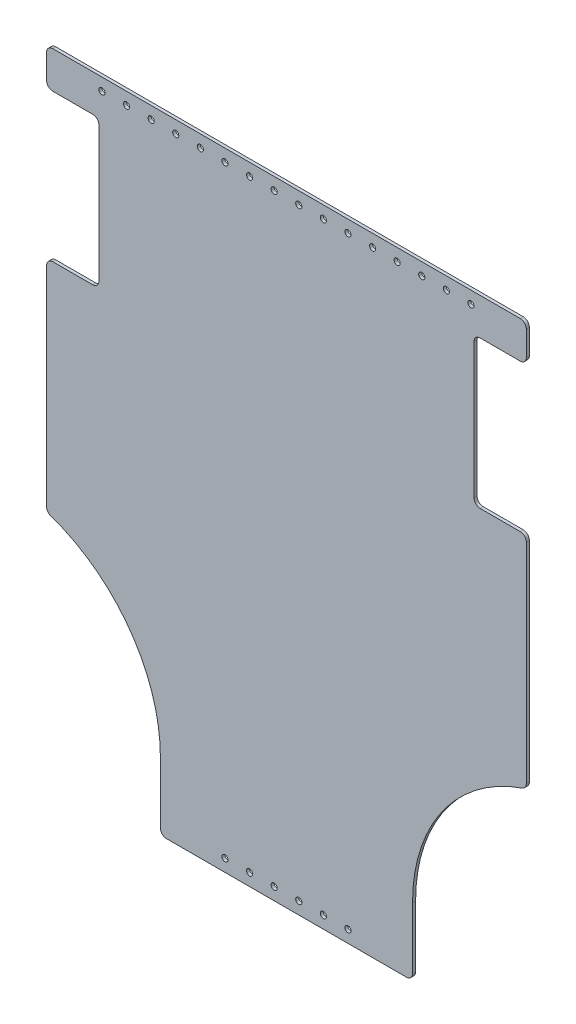
SolidWorks part; units mm, degrees
material "6061-T6 (SS)"
ref_plane "Front Plane" through (0, 0, 0) normal (0, 0, 1) x (1, 0, 0)
ref_plane "Top Plane" through (0, 0, 0) normal (0, 1, 0) x (1, 0, 0)
ref_plane "Right Plane" through (0, 0, 0) normal (1, 0, 0) x (0, 0, -1)
sketch "Sketch1" plane through (0, 0, 0) normal (0, 0, 1) x (1, 0, 0)
  line L0 (0, 0) -> (0, 19.5725) construction
  line L1 (-247.65, -317.5) -> (247.65, -317.5)
  line L2 (-247.65, -317.5) -> (-247.65, 317.5)
  line L3 (-247.65, 317.5) -> (247.65, 317.5)
  line L4 (247.65, -317.5) -> (247.65, 317.5)
  line L5 (-247.65, -317.5) -> (247.65, 317.5) construction
  line L6 (-247.65, 317.5) -> (247.65, -317.5) construction
  line L7 (247.65, 279.4) -> (193.675, 279.4)
  line L8 (247.65, 279.4) -> (247.65, 127)
  line L9 (247.65, 127) -> (193.675, 127)
  line L10 (193.675, 279.4) -> (193.675, 127)
  line L11 (-247.65, 127) -> (-193.675, 127)
  line L12 (-193.675, 279.4) -> (-193.675, 127)
  line L13 (-247.65, 279.4) -> (-193.675, 279.4)
  line L14 (-247.65, 279.4) -> (-247.65, 127)
  point P0 (0, 0)
  dimension "D1" = 495.3
  dimension "D2" = 635
  dimension "D3" = 38.1
  dimension "D4" = 190.5
  dimension "D5" = 53.975
extrude "Boss-Extrude1" add sketch "Sketch1" along normal blind 3.175 contours L2 L13 L12 L11 L1 L4 L9 L10 L7 L3
sketch "Sketch2" plane through (0, 0, 0) normal (0, 0, -1) x (-1, 0, 0)
  line L0 (0, -1000) -> (0, 49000) construction
  line L1 (247.65, -317.5) -> (-247.65, -317.5) construction
  line L2 (-130.175, -260.35) -> (-130.175, -324.3326)
  line L3 (-247.65, -317.5) -> (-247.65, 127) construction
  line L4 (-130.175, -324.3326) -> (-142.8136, -324.3326)
  line L5 (130.175, -324.3326) -> (142.8136, -324.3326)
  line L6 (130.175, -260.35) -> (130.175, -324.3326)
  arc A0 (-130.175, -260.35) -> (-142.8136, -324.3326) centre (-298.45, -260.35) ccw
  arc A1 (130.175, -260.35) -> (142.8136, -324.3326) centre (298.45, -260.35) cw
  dimension "D1" = 336.55
  dimension "D2" = 57.15
  dimension "D3" = 50.8
extrude "Cut-Extrude1" cut sketch "Sketch2" against normal through all
sketch "Sketch3" plane through (0, -317.5, 0) normal (0, -1, 0) x (1, 0, 0)
  line L4 (-130.175, 0) -> (130.175, 0)
  line L5 (130.175, 0) -> (130.175, 3.175)
  line L6 (130.175, 3.175) -> (-130.175, 3.175)
  line L7 (-130.175, 3.175) -> (-130.175, 0)
  line L8 (-130.175, 0) -> (130.175, 0)
  line L9 (130.175, 0) -> (130.175, 3.175)
  line L10 (130.175, 3.175) -> (-130.175, 3.175)
  line L11 (-130.175, 3.175) -> (-130.175, 0)
  dimension "D1" = 0
extrude "Boss-Extrude2" add sketch "Sketch3" along normal blind 12.7
fillet "Fillet1" radius 6.35 14 edges at (-247.65, -99.9261, 1.5875) (247.65, -99.9261, 1.5875) (193.675, 127, 1.5875) (193.675, 279.4, 1.5875) (-193.675, 279.4, 1.5875) (-193.675, 127, 1.5875) (247.65, 127, 1.5875) (-247.65, 127, 1.5875) (-247.65, 279.4, 1.5875) (-247.65, 317.5, 1.5875) (247.65, 317.5, 1.5875) (247.65, 279.4, 1.5875) (-130.175, -330.2, 1.5875) (130.175, -330.2, 1.5875)
sketch "Sketch5" plane through (0, 0, 0) normal (0, 0, -1) x (-1, 0, 0)
  line L0 (123.825, -330.2) -> (-123.825, -330.2) construction
  line L1 (0, -1330.2) -> (0, 48669.8) construction
  line L3 (241.3, 317.5) -> (-241.3, 317.5) construction
  circle A0 centre (-12.7, -317.5) radius 3.175
  circle A1 centre (12.7, -317.5) radius 3.175
  circle A2 centre (38.1, -317.5) radius 3.175
  circle A3 centre (63.5, -317.5) radius 3.175
  circle A4 centre (-12.7, -317.5) radius 3.175
  circle A5 centre (12.7, -317.5) radius 3.175
  circle A6 centre (38.1, -317.5) radius 3.175
  circle A7 centre (-38.1, -317.5) radius 3.175
  circle A8 centre (-12.7, -317.5) radius 3.175
  circle A9 centre (12.7, -317.5) radius 3.175
  circle A10 centre (-38.1, -317.5) radius 3.175
  circle A11 centre (-63.5, -317.5) radius 3.175
  circle A12 centre (-12.7, 304.8) radius 3.175
  circle A13 centre (12.7, 304.8) radius 3.175
  circle A14 centre (38.1, 304.8) radius 3.175
  circle A15 centre (63.5, 304.8) radius 3.175
  circle A16 centre (88.9, 304.8) radius 3.175
  circle A17 centre (114.3, 304.8) radius 3.175
  circle A18 centre (139.7, 304.8) radius 3.175
  circle A19 centre (165.1, 304.8) radius 3.175
  circle A20 centre (190.5, 304.8) radius 3.175
  circle A22 centre (-12.7, 304.8) radius 3.175
  circle A23 centre (12.7, 304.8) radius 3.175
  circle A24 centre (38.1, 304.8) radius 3.175
  circle A25 centre (63.5, 304.8) radius 3.175
  circle A26 centre (88.9, 304.8) radius 3.175
  circle A27 centre (114.3, 304.8) radius 3.175
  circle A28 centre (139.7, 304.8) radius 3.175
  circle A29 centre (165.1, 304.8) radius 3.175
  circle A30 centre (190.5, 304.8) radius 3.175
  circle A31 centre (-38.1, 304.8) radius 3.175
  circle A32 centre (-12.7, 304.8) radius 3.175
  circle A33 centre (12.7, 304.8) radius 3.175
  circle A34 centre (38.1, 304.8) radius 3.175
  circle A35 centre (63.5, 304.8) radius 3.175
  circle A36 centre (88.9, 304.8) radius 3.175
  circle A37 centre (114.3, 304.8) radius 3.175
  circle A38 centre (139.7, 304.8) radius 3.175
  circle A39 centre (165.1, 304.8) radius 3.175
  circle A40 centre (-63.5, 304.8) radius 3.175
  circle A41 centre (-38.1, 304.8) radius 3.175
  circle A42 centre (-12.7, 304.8) radius 3.175
  circle A43 centre (12.7, 304.8) radius 3.175
  circle A44 centre (38.1, 304.8) radius 3.175
  circle A45 centre (63.5, 304.8) radius 3.175
  circle A46 centre (88.9, 304.8) radius 3.175
  circle A47 centre (114.3, 304.8) radius 3.175
  circle A48 centre (139.7, 304.8) radius 3.175
  circle A49 centre (-88.9, 304.8) radius 3.175
  circle A50 centre (-63.5, 304.8) radius 3.175
  circle A51 centre (-38.1, 304.8) radius 3.175
  circle A52 centre (-12.7, 304.8) radius 3.175
  circle A53 centre (12.7, 304.8) radius 3.175
  circle A54 centre (38.1, 304.8) radius 3.175
  circle A55 centre (63.5, 304.8) radius 3.175
  circle A56 centre (88.9, 304.8) radius 3.175
  circle A57 centre (114.3, 304.8) radius 3.175
  circle A58 centre (-114.3, 304.8) radius 3.175
  circle A59 centre (-88.9, 304.8) radius 3.175
  circle A60 centre (-63.5, 304.8) radius 3.175
  circle A61 centre (-38.1, 304.8) radius 3.175
  circle A62 centre (-12.7, 304.8) radius 3.175
  circle A63 centre (12.7, 304.8) radius 3.175
  circle A64 centre (38.1, 304.8) radius 3.175
  circle A65 centre (63.5, 304.8) radius 3.175
  circle A66 centre (88.9, 304.8) radius 3.175
  circle A67 centre (-139.7, 304.8) radius 3.175
  circle A68 centre (-114.3, 304.8) radius 3.175
  circle A69 centre (-88.9, 304.8) radius 3.175
  circle A70 centre (-63.5, 304.8) radius 3.175
  circle A71 centre (-38.1, 304.8) radius 3.175
  circle A72 centre (-12.7, 304.8) radius 3.175
  circle A73 centre (12.7, 304.8) radius 3.175
  circle A74 centre (38.1, 304.8) radius 3.175
  circle A75 centre (63.5, 304.8) radius 3.175
  circle A76 centre (-165.1, 304.8) radius 3.175
  circle A77 centre (-139.7, 304.8) radius 3.175
  circle A78 centre (-114.3, 304.8) radius 3.175
  circle A79 centre (-88.9, 304.8) radius 3.175
  circle A80 centre (-63.5, 304.8) radius 3.175
  circle A81 centre (-38.1, 304.8) radius 3.175
  circle A82 centre (-12.7, 304.8) radius 3.175
  circle A83 centre (12.7, 304.8) radius 3.175
  circle A84 centre (38.1, 304.8) radius 3.175
  circle A85 centre (-190.5, 304.8) radius 3.175
  circle A86 centre (-165.1, 304.8) radius 3.175
  circle A87 centre (-139.7, 304.8) radius 3.175
  circle A88 centre (-114.3, 304.8) radius 3.175
  circle A89 centre (-88.9, 304.8) radius 3.175
  circle A90 centre (-63.5, 304.8) radius 3.175
  circle A91 centre (-38.1, 304.8) radius 3.175
  circle A92 centre (-12.7, 304.8) radius 3.175
  circle A93 centre (12.7, 304.8) radius 3.175
  circle A94 centre (-38.1, 304.8) radius 3.175
  circle A95 centre (-63.5, 304.8) radius 3.175
  circle A96 centre (-88.9, 304.8) radius 3.175
  circle A97 centre (-114.3, 304.8) radius 3.175
  circle A98 centre (-139.7, 304.8) radius 3.175
  circle A99 centre (-165.1, 304.8) radius 3.175
  circle A100 centre (-190.5, 304.8) radius 3.175
  circle A102 centre (215.9, 304.8) radius 3.175 [skipped]
  circle A103 centre (-215.9, 304.8) radius 3.175 [skipped]
  point P7 (0, -330.2)
  dimension "D1" = 12.7
  dimension "D2" = 12.7
  dimension "D5" = 6.35
  dimension "D6" = 6.35
  dimension "D7" = 12.7
  dimension "D8" = 12.7
  dimension "D3" = 4
  dimension "D4" = 3
  dimension "D9" = 10
  dimension "D10" = 9
extrude "Cut-Extrude2" cut sketch "Sketch5" against normal through all contours A3 | A2 | A1 | A0 | A7 | A11 | A20 | A19 | A18 | A17 | A16 | A15 | A14 | A13 | A12 | A31 | A40 | A49 | A58 | A67 | A76 | A85
sketch "Sketch6" plane through (0, 0, 3.175) normal (0, 0, 1) x (1, 0, 0)
  line L0 (123.825, -330.2) -> (-123.825, -330.2) construction
  line L1 (247.65, -95.3416) -> (247.65, 120.65) construction
  point P0 (247.65, -330.2)
